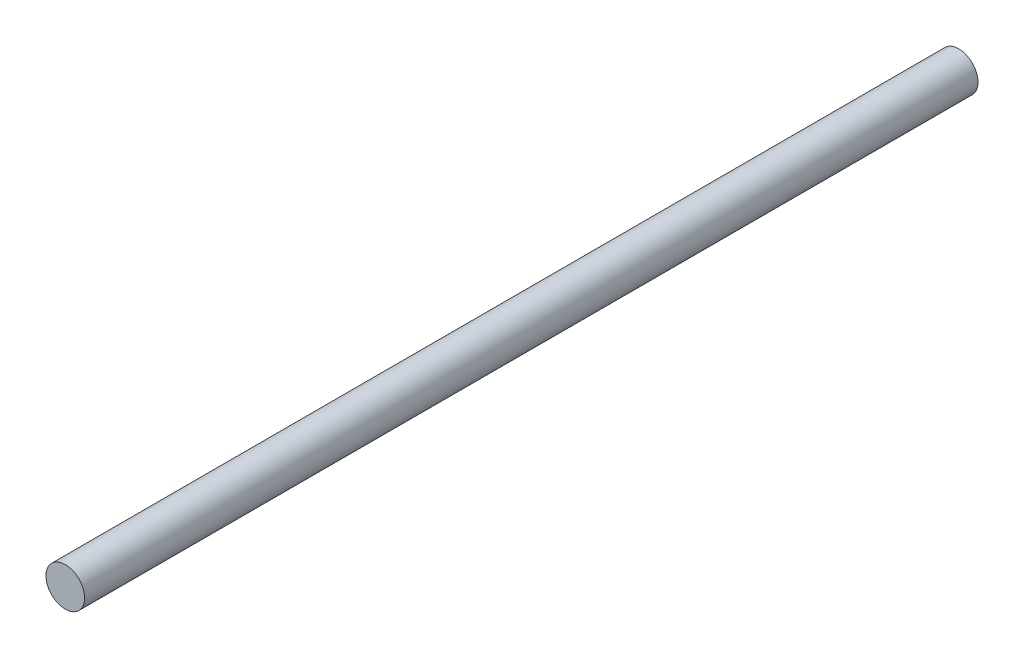
SolidWorks part; units mm, degrees
material "Nickel"
ref_plane "Front Plane" through (0, 0, 0) normal (0, 0, 1) x (1, 0, 0)
ref_plane "Top Plane" through (0, 0, 0) normal (0, 1, 0) x (1, 0, 0)
ref_plane "Right Plane" through (0, 0, 0) normal (1, 0, 0) x (0, 0, -1)
sketch "Sketch1" plane through (0, 0, 0) normal (0, 0, 1) x (1, 0, 0)
  circle A0 centre (-5.9871, 4.9645) radius 4
  dimension "D1" = 8
extrude "Boss-Extrude1" add sketch "Sketch1" along normal blind 185
